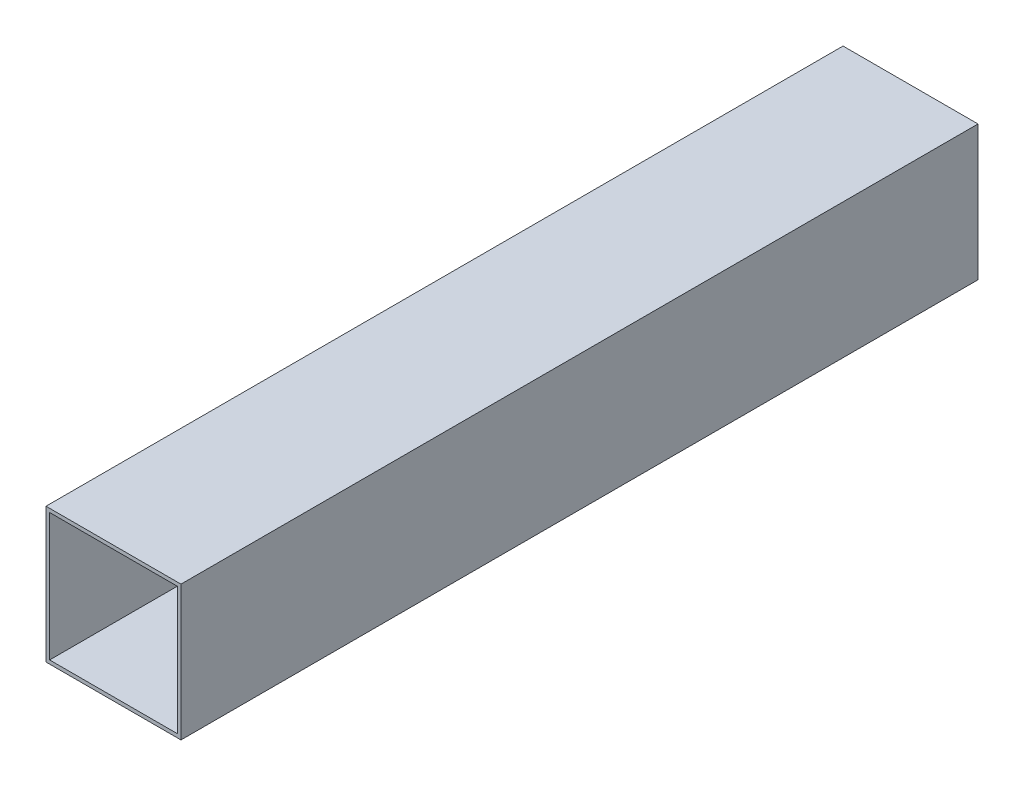
SolidWorks part; units mm, degrees
material "Aleación 1060"
ref_plane "Alzado" through (0, 0, 0) normal (0, 0, 1) x (1, 0, 0)
ref_plane "Planta" through (0, 0, 0) normal (0, 1, 0) x (1, 0, 0)
ref_plane "Vista lateral" through (0, 0, 0) normal (1, 0, 0) x (0, 0, -1)
sketch "Croquis1" plane through (0, 0, 0) normal (0, 0, 1) x (1, 0, 0)
  line L0 (-24.0284, -55.9716) -> (-24.0284, -104.0284)
  line L1 (-25.4, -54.6) -> (25.4, -54.6)
  line L2 (-25.4, -54.6) -> (-25.4, -105.4)
  line L3 (-25.4, -105.4) -> (25.4, -105.4)
  line L4 (25.4, -54.6) -> (25.4, -105.4)
  line L5 (-25.4, -54.6) -> (25.4, -105.4) construction
  line L6 (-25.4, -105.4) -> (25.4, -54.6) construction
  line L7 (-24.0284, -104.0284) -> (24.0284, -104.0284)
  line L8 (24.0284, -55.9716) -> (24.0284, -104.0284)
  line L9 (-24.0284, -55.9716) -> (24.0284, -55.9716)
  point P0 (0, -80)
  dimension "D1" = 80
  dimension "D2" = 50.8
  dimension "D3" = 50.8
  dimension "D4" = 1.3716
extrude "Saliente-Extruir1" add sketch "Croquis1" along normal blind 300
